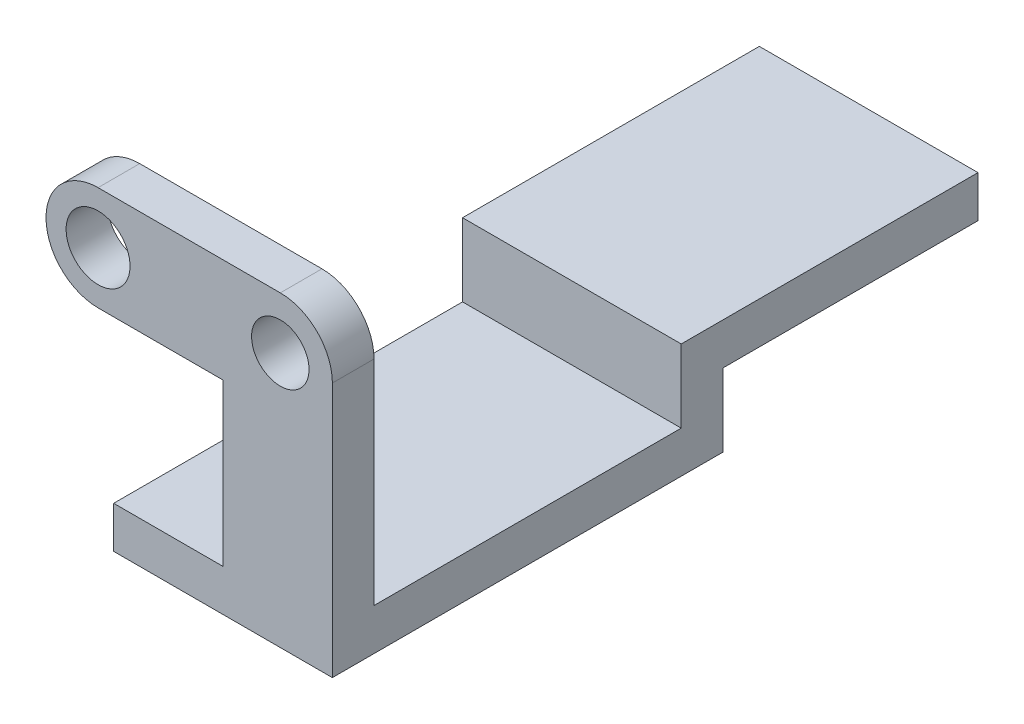
SolidWorks part; units mm, degrees
ref_plane "Front Plane" through (0, 0, 0) normal (0, 0, 1) x (1, 0, 0)
ref_plane "Top Plane" through (0, 0, 0) normal (0, 1, 0) x (1, 0, 0)
ref_plane "Right Plane" through (0, 0, 0) normal (1, 0, 0) x (0, 0, -1)
sketch "Sketch10" plane through (0, 0, 0) normal (1, 0, 0) x (0, 0, -1)
  line L0 (-150, 0) -> (0, 0)
  line L1 (0, 0) -> (0, 28)
  line L2 (0, 28) -> (98, 28)
  line L3 (98, 28) -> (98, 44)
  line L4 (98, 44) -> (-16, 44)
  line L5 (-16, 44) -> (-16, 16)
  line L6 (-16, 16) -> (-150, 16)
  line L7 (-150, 16) -> (-150, 0)
  point P5 (-152.6239, 0)
  dimension "D1" = 150
  dimension "D2" = 16
  dimension "D3" = 98
  dimension "D4" = 114
  dimension "D5" = 16
  dimension "D6" = 28
extrude "Boss-Extrude1" add sketch "Sketch10" along normal mid plane 84
sketch "Sketch11" plane through (0, 16, 0) normal (0, 1, 0) x (1, 0, 0)
  line L1 (0, -134) -> (42, -134)
  line L2 (0, -134) -> (0, -150)
  line L3 (0, -150) -> (42, -150)
  line L4 (-42, -16) -> (-42, -150)
  line L5 (-42, -150) -> (42, -150)
  line L6 (42, -150) -> (42, -16)
  line L7 (42, -16) -> (-42, -16)
  line L8 (-42, -16) -> (-42, -150)
  line L9 (-42, -150) -> (42, -150)
  line L10 (42, -150) -> (42, -16)
  line L11 (42, -16) -> (-42, -16)
  line L12 (42, -134) -> (42, -150)
  line L13 (0, -134) -> (42, -150) construction
  line L14 (0, -150) -> (42, -134) construction
  point P2 (21, -142)
  line M10 (-42, -150) -> (42, -150)
  line M11 (42, -150) -> (42, -16)
  dimension "D2" = 42
  dimension "D3" = 16
  dimension "D1" = 0
extrude "Boss-Extrude2" add sketch "Sketch11" along normal blind 82 contours L1 L2 M10 M11
sketch "Sketch12" plane through (0, 0, 150) normal (0, 0, 1) x (1, 0, 0)
  line L0 (-48, 98) -> (22, 98) construction
  line L1 (-48, 118) -> (22, 118)
  line L2 (-48, 78) -> (22, 78)
  line L6 (-42, 16) -> (-42, 0)
  line L7 (-42, 0) -> (42, 0)
  line L8 (42, 0) -> (42, 98)
  line L9 (42, 98) -> (0, 98)
  line L10 (0, 98) -> (0, 16)
  line L11 (0, 16) -> (-42, 16)
  line L12 (-42, 16) -> (-42, 0)
  line L13 (-42, 0) -> (42, 0)
  line L14 (42, 0) -> (42, 98)
  line L15 (42, 98) -> (0, 98)
  line L16 (0, 98) -> (0, 16)
  line L17 (0, 16) -> (-42, 16)
  arc A0 (-48, 118) -> (-48, 78) centre (-48, 98) ccw
  arc A1 (22, 78) -> (22, 118) centre (22, 98) ccw
  point P6 (-13, 98)
  dimension "D3" = 20
  dimension "D2" = 70
  dimension "D1" = 0
extrude "Boss-Extrude4" add sketch "Sketch12" against normal up to surface (16 mm away) up to face at (21, 57, 134)
sketch "Sketch17" plane through (0, 0, 134) normal (0, 0, -1) x (-1, 0, 0)
  line L5 (0, 16) -> (0, 78)
  line L6 (0, 78) -> (48, 78)
  line L7 (48, 118) -> (-22, 118)
  line L8 (-42, 98) -> (-42, 16)
  line L9 (-42, 16) -> (0, 16)
  line L10 (0, 16) -> (0, 78)
  line L11 (0, 78) -> (48, 78)
  line L12 (48, 118) -> (-22, 118)
  line L13 (-42, 98) -> (-42, 16)
  line L14 (-42, 16) -> (0, 16)
  circle A0 centre (-22, 98) radius 11.0343
  circle A1 centre (48, 98) radius 12.2802
  arc A2 (48, 78) -> (48, 118) centre (48, 98) ccw
  arc A3 (-22, 118) -> (-42, 98) centre (-22, 98) ccw
  arc A4 (48, 78) -> (48, 118) centre (48, 98) ccw
  arc A5 (-22, 118) -> (-42, 98) centre (-22, 98) ccw
  dimension "D1" = 0
extrude "Cut-Extrude2" cut sketch "Sketch17" against normal through all both and the other way through all contours A0 | A1
